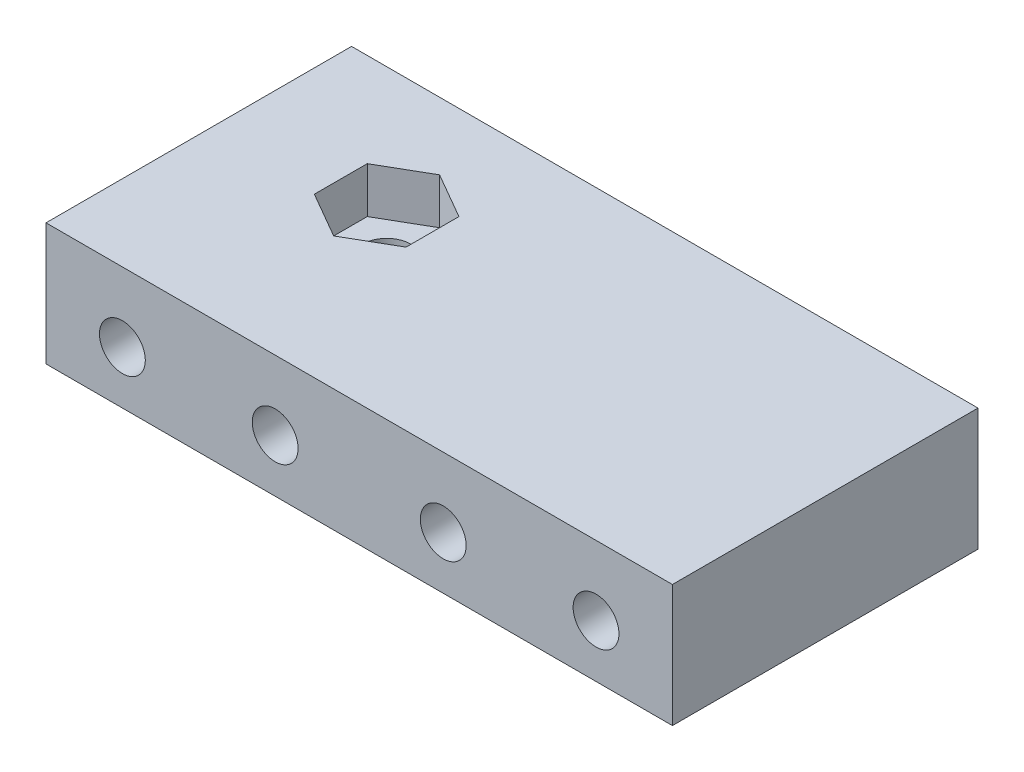
SolidWorks part; units mm, degrees
ref_plane "Front Plane" through (0, 0, 0) normal (0, 0, 1) x (1, 0, 0)
ref_plane "Top Plane" through (0, 0, 0) normal (0, 1, 0) x (1, 0, 0)
ref_plane "Right Plane" through (0, 0, 0) normal (1, 0, 0) x (0, 0, -1)
sketch "Sketch1" plane through (0, 0, 0) normal (0, 1, 0) x (1, 0, 0)
  line L1 (0, 0) -> (41, 0)
  line L2 (0, 0) -> (0, 20)
  line L3 (0, 20) -> (41, 20)
  line L4 (41, 0) -> (41, 20)
  dimension "D1" = 20
  dimension "D2" = 41
extrude "Boss-Extrude1" add sketch "Sketch1" along normal blind 8
sketch "Sketch2" plane through (0, 0, 0) normal (0, 0, 1) x (1, 0, 0)
  line L1 (0, 8) -> (0, 0) construction
  line L2 (41, 8) -> (0, 8) construction
  circle A0 centre (5, 3.455) radius 1.5
  dimension "D1" = 3
  dimension "D3" = 5
  dimension "D2" = 4.545
extrude "Cut-Extrude1" cut sketch "Sketch2" against normal through all
pattern_linear "LPattern1" count 2 spacing 10 along (1, 0, 0) of "Cut-Extrude1"
pattern_linear "LPattern2" count 2 spacing 21 along (1, 0, 0) of "Cut-Extrude1"
pattern_linear "LPattern3" count 2 spacing 31 along (1, 0, 0) of "Cut-Extrude1"
sketch "Sketch3" plane through (0, 0, 0) normal (0, 1, 0) x (1, 0, 0)
  line L0 (0, 20) -> (0, 0) construction
  line L9 (0, 0) -> (41, 0) construction
  circle A1 centre (10.16, 12.135) radius 3
  circle A6 centre (10.16, 12.135) radius 1.6
  dimension "D2" = 6
  dimension "D3" = 12.135
  dimension "D4" = 3.2
  dimension "D1" = 10.16
extrude "Cut-Extrude6" cut sketch "Sketch3" along normal through all contours A6
sketch "Sketch13" plane through (0, 0, 0) normal (0, -1, 0) x (1, 0, 0)
  circle A0 centre (10.16, -12.135) radius 3.5
  circle A1 centre (10.16, -12.135) radius 1.6 construction
  circle A2 centre (10.16, -12.135) radius 1.6
  dimension "D1" = 7
extrude "Boss-Extrude6" add sketch "Sketch13" along normal blind 2.5
sketch "Sketch14" plane through (0, 8, 0) normal (0, 1, 0) x (1, 0, 0)
  line L1 (7.16, 10.4029) -> (10.16, 8.6709)
  line L2 (10.16, 8.6709) -> (13.16, 10.4029)
  line L3 (13.16, 10.4029) -> (13.16, 13.8671)
  line L4 (13.16, 13.8671) -> (10.16, 15.5991)
  line L5 (10.16, 15.5991) -> (7.16, 13.8671)
  line L6 (7.16, 13.8671) -> (7.16, 10.4029)
  circle A0 centre (10.16, 12.135) radius 3 construction
  dimension "D1" = 6
extrude "Cut-Extrude7" cut sketch "Sketch14" against normal blind 3
move or copy body "Body-Move/Copy1" [suppressed] bodies to move or copy 118
equation "\"D2@Sketch2\"=(8-2.39+3.48)/2"
